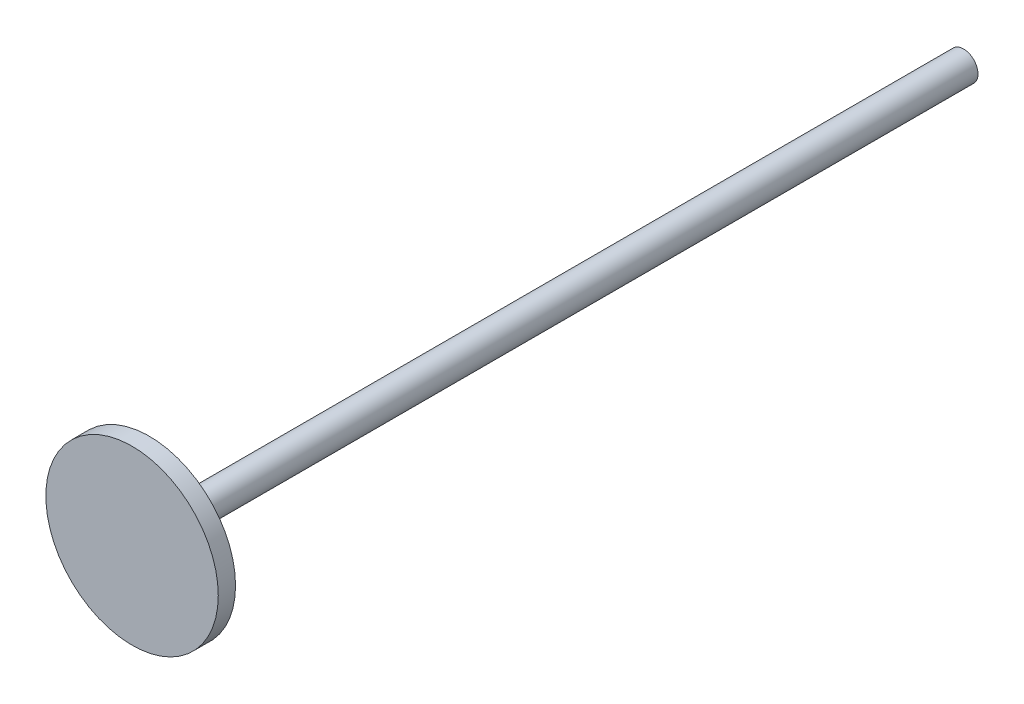
SolidWorks part; units mm, degrees
other "Markup1"
sketch "Sketch6" plane through (-23.8535, 23.8535, 0) normal (-0.0708, 0.9883, -0.1352) x (0.9909, 0.0853, 0.1045)
sketch "Sketch7" plane through (-23.8535, 23.8535, 0) normal (-0.0708, 0.9883, -0.1352) x (0.9909, 0.0853, 0.1045)
sketch "Sketch8" plane through (-23.8535, 23.8535, 0) normal (-0.0708, 0.9883, -0.1352) x (0.9909, 0.0853, 0.1045)
sketch "Sketch9" plane through (-23.8535, 23.8535, 0) normal (-0.0708, 0.9883, -0.1352) x (0.9909, 0.0853, 0.1045)
sketch "Sketch10" plane through (-23.8535, 23.8535, 0) normal (-0.0708, 0.9883, -0.1352) x (0.9909, 0.0853, 0.1045)
sketch "Sketch11" plane through (-23.8535, 23.8535, 0) normal (-0.0708, 0.9883, -0.1352) x (0.9909, 0.0853, 0.1045)
sketch "Sketch12" plane through (-23.8535, 23.8535, 0) normal (-0.0708, 0.9883, -0.1352) x (0.9909, 0.0853, 0.1045)
sketch "Sketch13" plane through (-23.8535, 23.8535, 0) normal (-0.0708, 0.9883, -0.1352) x (0.9909, 0.0853, 0.1045)
sketch "Sketch14" plane through (-23.8535, 23.8535, 0) normal (-0.0708, 0.9883, -0.1352) x (0.9909, 0.0853, 0.1045)
sketch "Sketch15" plane through (-23.8535, 23.8535, 0) normal (-0.0708, 0.9883, -0.1352) x (0.9909, 0.0853, 0.1045)
ref_plane "Front Plane" through (0, 0, 0) normal (0, 0, 1) x (1, 0, 0)
ref_plane "Top Plane" through (0, 0, 0) normal (0, 1, 0) x (1, 0, 0)
ref_plane "Right Plane" through (0, 0, 0) normal (1, 0, 0) x (0, 0, -1)
sketch "Sketch1" plane through (0, 0, 0) normal (0, 0, 1) x (1, 0, 0)
  circle A0 centre (0, 0) radius 23.85
  dimension "D1" = 47.7
extrude "Boss-Extrude1" add sketch "Sketch1" along normal blind 230
sketch "Sketch2" plane through (0, 0, 0) normal (0, 0, 1) x (1, 0, 0)
  circle A0 centre (0, 0) radius 4
  dimension "D1" = 8
extrude "Cut-Extrude1" cut sketch "Sketch2" along normal blind 218 flip side to cut
sketch "Sketch5" plane through (0, 0, 0) normal (0, 1, 0) x (1, 0, 0)
  line L0 (4, -218) -> (23.85, -225.2248)
  line L1 (23.85, -230) -> (23.85, -218) construction
  line L2 (23.85, -225.2248) -> (23.85, -218)
  line L3 (23.85, -218) -> (4, -218)
  line L4 (0, 0) -> (0, -87.7891) construction
  dimension "D1" = 70
  dimension "D2" = 7.2248
revolve "Cut-Revolve1" cut sketch "Sketch5" angle 360 about L4
equation "\"D1@Sketch1\"=0.0477"
equation "\"D1@Boss-Extrude1\"=230mm"
